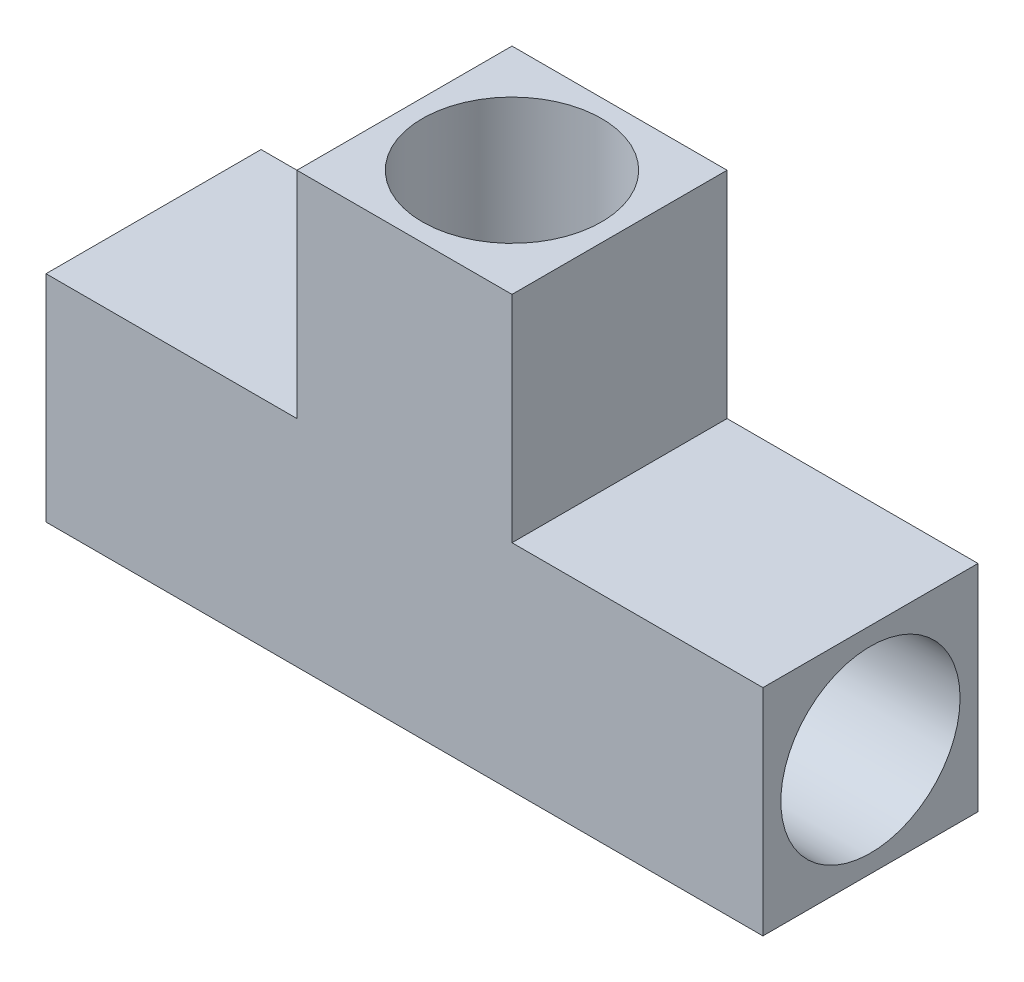
SolidWorks part; units mm, degrees
ref_plane "前视基准面" through (0, 0, 0) normal (0, 0, 1) x (1, 0, 0)
ref_plane "上视基准面" through (0, 0, 0) normal (0, 1, 0) x (1, 0, 0)
ref_plane "右视基准面" through (0, 0, 0) normal (1, 0, 0) x (0, 0, -1)
sketch "草图5" plane through (0, 0, 0) normal (0, 0, 1) x (1, 0, 0)
  line L0 (15, 15) -> (50, 15)
  line L1 (-50, 15) -> (-15, 15)
  line L2 (-50, 15) -> (-50, -15)
  line L3 (-50, -15) -> (50, -15)
  line L4 (50, 15) -> (50, -15)
  line L5 (-50, 15) -> (50, -15) construction
  line L6 (-50, -15) -> (50, 15) construction
  line L7 (-15, 45) -> (15, 45)
  line L8 (-15, 45) -> (-15, 15)
  line L10 (15, 45) -> (15, 15)
  point P0 (0, 0)
  point P10 (0, 45)
  dimension "D1" = 100
  dimension "D2" = 30
  dimension "D3" = 30
  dimension "D4" = 30
extrude "凸台-拉伸3" add sketch "草图5" along normal mid plane 30
sketch "草图6" plane through (50, 0, 0) normal (1, 0, 0) x (0, 0, -1)
  circle A0 centre (0, 0) radius 12.5
  dimension "D1" = 25
extrude "切除-拉伸3" cut sketch "草图6" against normal blind 100
sketch "草图7" plane through (0, 45, 0) normal (0, 1, 0) x (1, 0, 0)
  circle A0 centre (0, 0) radius 12.5
  dimension "D1" = 25
extrude "切除-拉伸4" cut sketch "草图7" against normal blind 45
